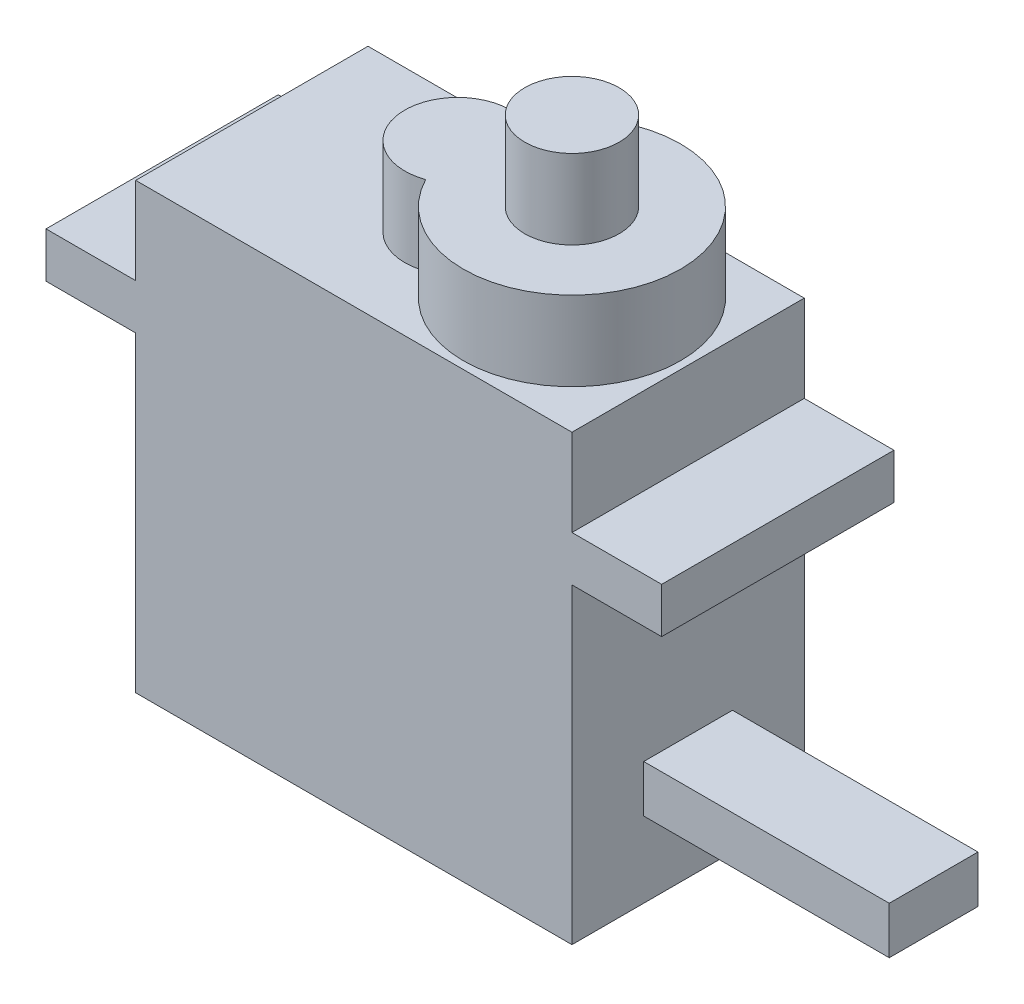
SolidWorks part; units mm, degrees
ref_plane "前视基准面" through (0, 0, 0) normal (0, 0, 1) x (1, 0, 0)
ref_plane "上视基准面" through (0, 0, 0) normal (0, 1, 0) x (1, 0, 0)
ref_plane "右视基准面" through (0, 0, 0) normal (1, 0, 0) x (0, 0, -1)
sketch "草图1" plane through (0, 0, 0) normal (0, 0, 1) x (1, 0, 0)
  line L1 (-11.55, 11.75) -> (11.55, 11.75)
  line L2 (-11.55, 11.75) -> (-11.55, -11.75)
  line L3 (-11.55, -11.75) -> (11.55, -11.75)
  line L4 (11.55, 11.75) -> (11.55, -11.75)
  line L5 (-11.55, 11.75) -> (11.55, -11.75) construction
  line L6 (-11.55, -11.75) -> (11.55, 11.75) construction
  line L7 (-16.3, 7.15) -> (16.3, 7.15)
  line L8 (-16.3, 7.15) -> (-16.3, 4.75)
  line L9 (-16.3, 4.75) -> (16.3, 4.75)
  line L10 (16.3, 7.15) -> (16.3, 4.75)
  point P0 (0, 0)
  dimension "D1" = 23.5
  dimension "D2" = 23.1
  dimension "D3" = 2.4
  dimension "D4" = 7
  dimension "D5" = 32.6
  dimension "D6" = 16.3
extrude "凸台-拉伸1" add sketch "草图1" along normal blind 12.3 contours L2 L7 L4 L1 | L2 L9 L4 L7 | L8 L9 L2 L7 | L10 L7 L4 L9 | L9 L2 L3 L4
sketch "草图2" plane through (0, 11.75, 0) normal (0, 1, 0) x (1, 0, 0)
  line L0 (-11.55, 0) -> (11.55, -12.3) construction
  line L1 (11.55, 0) -> (-11.55, -12.3) construction
  line L2 (-11.55, -6.15) -> (11.55, -6.15) construction
  line L4 (11.55, 0) -> (-11.55, 0)
  line L5 (-11.55, 0) -> (-11.55, -12.3)
  line L6 (-11.55, -12.3) -> (11.55, -12.3)
  line L7 (11.55, -12.3) -> (11.55, 0)
  line L8 (11.55, 0) -> (-11.55, 0)
  line L9 (-11.55, 0) -> (-11.55, -12.3)
  line L10 (-11.55, -12.3) -> (11.55, -12.3)
  line L11 (11.55, -12.3) -> (11.55, 0)
  circle A0 centre (5.4, -6.15) radius 5.75
  circle A1 centre (-0.65, -6.15) radius 2.8
  dimension "D2" = 6.15
  dimension "D4" = 6.05
  dimension "D3" = 6.15
  dimension "D1" = 0
extrude "凸台-拉伸3" add sketch "草图2" along normal blind 4.2 contours A0 A1 | A1 A0 | A0 A1
sketch "草图4" plane through (0, 15.95, 0) normal (0, 1, 0) x (1, 0, 0)
  circle A0 centre (5.4, -6.15) radius 2.5
  arc A2 (0.2905, -3.5127) -> (0.2905, -8.7873) centre (-0.65, -6.15) ccw
  arc A3 (0.2905, -8.7873) -> (0.2905, -3.5127) centre (5.4, -6.15) ccw
  arc A4 (0.2905, -3.5127) -> (0.2905, -8.7873) centre (-0.65, -6.15) ccw
  arc A5 (0.2905, -8.7873) -> (0.2905, -3.5127) centre (5.4, -6.15) ccw
  dimension "D1" = 0
extrude "凸台-拉伸4" add sketch "草图4" along normal blind 4.2 contours A0
sketch "草图5" plane through (11.55, 0, 0) normal (1, 0, 0) x (0, 0, -1)
  line L0 (-12.2201, 4.75) -> (0, -11.75) construction
  line L1 (-12.3, -11.75) -> (0, 4.75) construction
  line L2 (-6.15, 4.75) -> (-6.15, -11.75) construction
  line L4 (0, -11.75) -> (0, 4.75)
  line L5 (0, 4.75) -> (-12.3, 4.75)
  line L6 (-12.3, 4.75) -> (-12.3, -11.75)
  line L7 (-12.3, -11.75) -> (0, -11.75)
  line L8 (0, -11.75) -> (0, 4.75)
  line L9 (0, 4.75) -> (-12.3, 4.75)
  line L10 (-12.3, 4.75) -> (-12.3, -11.75)
  line L11 (-12.3, -11.75) -> (0, -11.75)
  line L12 (-8.5, -5.25) -> (-3.8, -5.25)
  line L13 (-8.5, -5.25) -> (-8.5, -7.75)
  line L14 (-8.5, -7.75) -> (-3.8, -7.75)
  line L15 (-3.8, -5.25) -> (-3.8, -7.75)
  line L16 (-8.5, -5.25) -> (-3.8, -7.75) construction
  line L17 (-8.5, -7.75) -> (-3.8, -5.25) construction
  point P7 (-6.15, -6.5)
  dimension "D2" = 2.5
  dimension "D3" = 6.5
  dimension "D4" = 4.7
  dimension "D5" = 6.15
  dimension "D1" = 0
extrude "凸台-拉伸5" add sketch "草图5" along normal blind 8 contours L13 L12 L15 L14
sketch "草图6" plane through (19.55, 0, 0) normal (1, 0, 0) x (0, 0, -1)
  line L4 (-8.5, -7.75) -> (-3.8, -7.75)
  line L5 (-3.8, -7.75) -> (-3.8, -5.25)
  line L6 (-3.8, -5.25) -> (-8.5, -5.25)
  line L7 (-8.5, -5.25) -> (-8.5, -7.75)
  line L8 (-8.5, -7.75) -> (-3.8, -7.75)
  line L9 (-3.8, -7.75) -> (-3.8, -5.25)
  line L10 (-3.8, -5.25) -> (-8.5, -5.25)
  line L11 (-8.5, -5.25) -> (-8.5, -7.75)
  dimension "D1" = 0
extrude "凸台-拉伸6" add sketch "草图6" along normal blind 5 contours L8 L9 L10 L11
sketch "草图7" plane through (0, 7.15, 0) normal (0, 1, 0) x (1, 0, 0)
  line L0 (-11.55, -6.15) -> (-16.3, -6.15) construction
  line L1 (-13.925, 0) -> (-13.925, -12.3) construction
  line L4 (-11.55, 0) -> (-16.3, 0)
  line L5 (-16.3, 0) -> (-16.3, -12.3)
  line L6 (-16.3, -12.3) -> (-11.55, -12.3)
  line L7 (-11.55, -12.3) -> (-11.55, 0)
  line L8 (-11.55, 0) -> (-16.3, 0)
  line L9 (-16.3, 0) -> (-16.3, -12.3)
  line L10 (-16.3, -12.3) -> (-11.55, -12.3)
  line L11 (-11.55, -12.3) -> (-11.55, 0)
  circle A0 centre (-13.925, -6.15) radius 0.965
  dimension "D2" = 1.93
  dimension "D1" = 0
extrude "切除-拉伸1" cut sketch "草图7" against normal blind 7 contours A0
